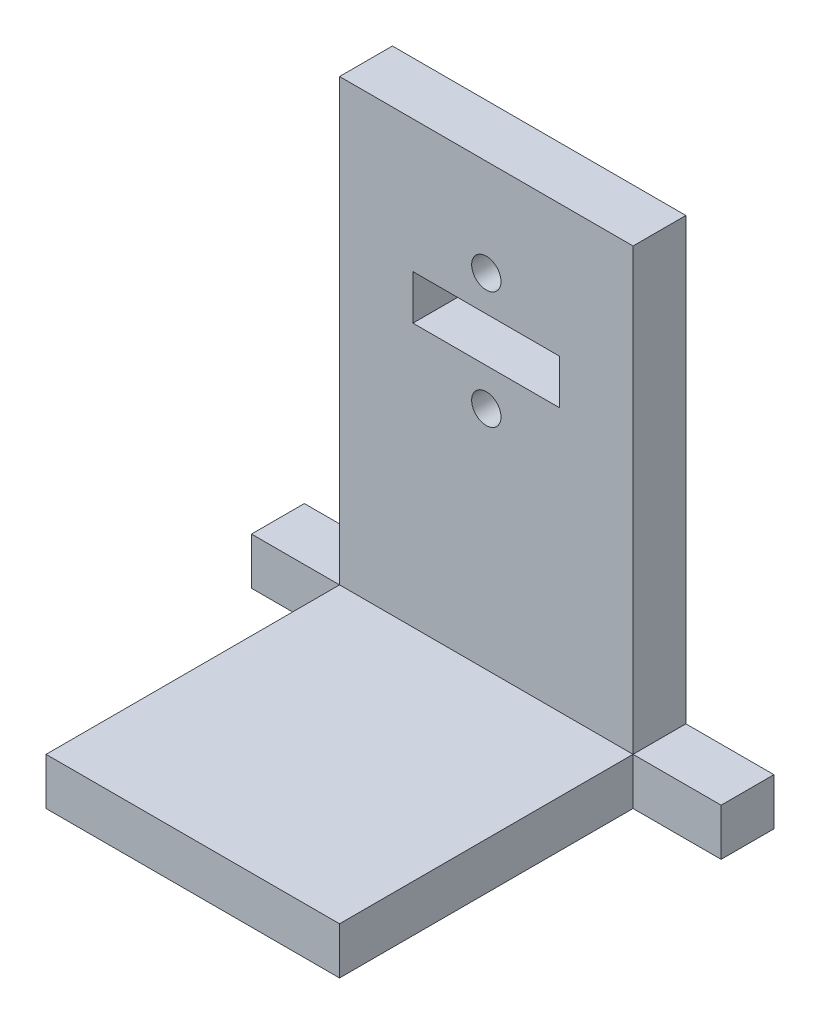
SolidWorks part; units mm, degrees
ref_plane "Plan de face" through (0, 0, 0) normal (0, 0, 1) x (1, 0, 0)
ref_plane "Plan de dessus" through (0, 0, 0) normal (0, 1, 0) x (1, 0, 0)
ref_plane "Plan de droite" through (0, 0, 0) normal (1, 0, 0) x (0, 0, -1)
sketch "Esquisse1" plane through (0, 0, 0) normal (0, 0, 1) x (1, 0, 0)
  line L0 (1.5532, 0) -> (81.5532, 0)
  line L1 (81.5532, 0) -> (81.5532, 8)
  line L2 (81.5532, 8) -> (66.5532, 8)
  line L3 (66.5532, 8) -> (66.5532, 83)
  line L4 (66.5532, 83) -> (16.5532, 83)
  line L5 (16.5532, 83) -> (16.5532, 8)
  line L6 (16.5532, 8) -> (1.5532, 8)
  line L7 (1.5532, 8) -> (1.5532, 0)
  line L8 (54.0532, 60.4724) -> (54.0532, 52.8632)
  line L9 (29.0532, 52.8632) -> (54.0532, 52.8632)
  line L11 (54.0532, 60.4724) -> (29.0532, 60.4724)
  line L12 (29.0532, 60.4724) -> (29.0532, 52.8632)
  circle A0 centre (41.5532, 46.5) radius 2.5
  circle A1 centre (41.5532, 66.5) radius 2.5
  dimension "D7" = 5
  dimension "D8" = 5
  dimension "D10" = 20
  dimension "D1" = 8
  dimension "D2" = 8
  dimension "D3" = 15
  dimension "D4" = 15
  dimension "D5" = 50
  dimension "D6" = 75
  dimension "D9" = 46.5
  dimension "D11" = 25
  dimension "D12" = 25
  dimension "D13" = 12.5
  dimension "D14" = 25
  dimension "D15" = 25
extrude "Boss.-Extru.1" add sketch "Esquisse1" against normal blind 9
sketch "Esquisse2" plane through (0, 0, 0) normal (0, 0, 1) x (1, 0, 0)
  line L0 (1.5532, 0) -> (81.5532, 0) construction
  line L1 (16.5532, 8) -> (66.5507, 8)
  line L2 (16.5532, 8) -> (16.5532, 0)
  line L3 (16.5532, 0) -> (66.5507, 0)
  line L4 (66.5507, 8) -> (66.5507, 0)
extrude "Boss.-Extru.2" add sketch "Esquisse2" along normal blind 50
